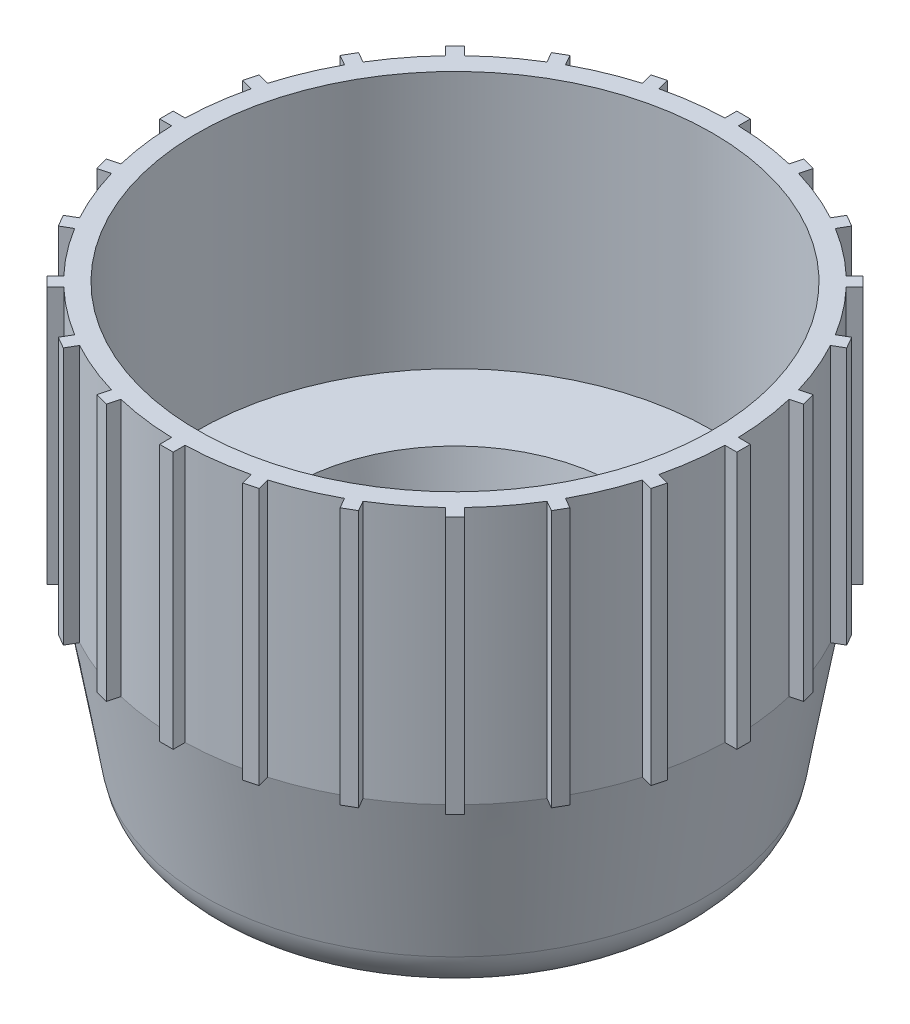
SolidWorks part; units mm, degrees
ref_plane "Front Plane" through (0, 0, 0) normal (0, 0, 1) x (1, 0, 0)
ref_plane "Top Plane" through (0, 0, 0) normal (0, 1, 0) x (1, 0, 0)
ref_plane "Right Plane" through (0, 0, 0) normal (1, 0, 0) x (0, 0, -1)
sketch "Sketch1" plane through (0, 0, 0) normal (0, 0, 1) x (1, 0, 0)
  line L0 (0, 0) -> (0, 35) construction
  line L1 (0, 0) -> (15.4987, 0)
  line L2 (19.4379, 3.3054) -> (21.5, 15)
  line L3 (10, 0) -> (12.6449, 15)
  line L4 (12.6449, 15) -> (20, 15)
  line L5 (20, 15) -> (20, 35)
  line L6 (20, 35) -> (21.5, 35)
  line L7 (21.5, 35) -> (21.5, 15)
  arc A0 (15.4987, 0) -> (19.4379, 3.3054) centre (15.4987, 4) ccw
  dimension "D8" = 4
  dimension "D1" = 35
  dimension "D2" = 20
  dimension "D3" = 100
  dimension "D4" = 20
  dimension "D5" = 40
  dimension "D6" = 43
  dimension "D7" = 80
revolve "Revolve1" add sketch "Sketch1" angle 360 about L0
sketch "Sketch2" plane through (0, 35, 0) normal (0, 1, 0) x (1, 0, 0)
  line L0 (21.4936, -0.525) -> (22.42, -0.525)
  line L1 (22.42, -0.525) -> (22.42, 0.525)
  line L2 (22.42, 0.525) -> (21.4936, 0.525)
  line L3 (20.6253, -6.0701) -> (21.5202, -6.3098)
  line L4 (21.7919, -5.2956) -> (20.8971, -5.0558)
  line L5 (21.5202, -6.3098) -> (21.7919, -5.2956)
  line L6 (18.3515, -11.2015) -> (19.1538, -11.6647)
  line L7 (19.6788, -10.7553) -> (18.8765, -10.2921)
  line L8 (19.1538, -11.6647) -> (19.6788, -10.7553)
  line L9 (14.827, -15.5695) -> (15.4821, -16.2246)
  line L10 (16.2246, -15.4821) -> (15.5695, -14.827)
  line L11 (15.4821, -16.2246) -> (16.2246, -15.4821)
  line L12 (10.2921, -18.8765) -> (10.7553, -19.6788)
  line L13 (11.6647, -19.1538) -> (11.2015, -18.3515)
  line L14 (10.7553, -19.6788) -> (11.6647, -19.1538)
  line L15 (5.0558, -20.8971) -> (5.2956, -21.7919)
  line L16 (6.3098, -21.5202) -> (6.0701, -20.6253)
  line L17 (5.2956, -21.7919) -> (6.3098, -21.5202)
  line L18 (-0.525, -21.4936) -> (-0.525, -22.42)
  line L19 (0.525, -22.42) -> (0.525, -21.4936)
  line L20 (-0.525, -22.42) -> (0.525, -22.42)
  line L21 (-6.0701, -20.6253) -> (-6.3098, -21.5202)
  line L22 (-5.2956, -21.7919) -> (-5.0558, -20.8971)
  line L23 (-6.3098, -21.5202) -> (-5.2956, -21.7919)
  line L24 (-11.2015, -18.3515) -> (-11.6647, -19.1538)
  line L25 (-10.7553, -19.6788) -> (-10.2921, -18.8765)
  line L26 (-11.6647, -19.1538) -> (-10.7553, -19.6788)
  line L27 (-15.5695, -14.827) -> (-16.2246, -15.4821)
  line L28 (-15.4821, -16.2246) -> (-14.827, -15.5695)
  line L29 (-16.2246, -15.4821) -> (-15.4821, -16.2246)
  line L30 (-18.8765, -10.2921) -> (-19.6788, -10.7553)
  line L31 (-19.1538, -11.6647) -> (-18.3515, -11.2015)
  line L32 (-19.6788, -10.7553) -> (-19.1538, -11.6647)
  line L33 (-20.8971, -5.0558) -> (-21.7919, -5.2956)
  line L34 (-21.5202, -6.3098) -> (-20.6253, -6.0701)
  line L35 (-21.7919, -5.2956) -> (-21.5202, -6.3098)
  line L36 (-21.4936, 0.525) -> (-22.42, 0.525)
  line L37 (-22.42, -0.525) -> (-21.4936, -0.525)
  line L38 (-22.42, 0.525) -> (-22.42, -0.525)
  line L39 (-20.6253, 6.0701) -> (-21.5202, 6.3098)
  line L40 (-21.7919, 5.2956) -> (-20.8971, 5.0558)
  line L41 (-21.5202, 6.3098) -> (-21.7919, 5.2956)
  line L42 (-18.3515, 11.2015) -> (-19.1538, 11.6647)
  line L43 (-19.6788, 10.7553) -> (-18.8765, 10.2921)
  line L44 (-19.1538, 11.6647) -> (-19.6788, 10.7553)
  line L45 (-14.827, 15.5695) -> (-15.4821, 16.2246)
  line L46 (-16.2246, 15.4821) -> (-15.5695, 14.827)
  line L47 (-15.4821, 16.2246) -> (-16.2246, 15.4821)
  line L48 (-10.2921, 18.8765) -> (-10.7553, 19.6788)
  line L49 (-11.6647, 19.1538) -> (-11.2015, 18.3515)
  line L50 (-10.7553, 19.6788) -> (-11.6647, 19.1538)
  line L51 (-5.0558, 20.8971) -> (-5.2956, 21.7919)
  line L52 (-6.3098, 21.5202) -> (-6.0701, 20.6253)
  line L53 (-5.2956, 21.7919) -> (-6.3098, 21.5202)
  line L54 (0.525, 21.4936) -> (0.525, 22.42)
  line L55 (-0.525, 22.42) -> (-0.525, 21.4936)
  line L56 (0.525, 22.42) -> (-0.525, 22.42)
  line L57 (6.0701, 20.6253) -> (6.3098, 21.5202)
  line L58 (5.2956, 21.7919) -> (5.0558, 20.8971)
  line L59 (6.3098, 21.5202) -> (5.2956, 21.7919)
  line L60 (11.2015, 18.3515) -> (11.6647, 19.1538)
  line L61 (10.7553, 19.6788) -> (10.2921, 18.8765)
  line L62 (11.6647, 19.1538) -> (10.7553, 19.6788)
  line L63 (15.5695, 14.827) -> (16.2246, 15.4821)
  line L64 (15.4821, 16.2246) -> (14.827, 15.5695)
  line L65 (16.2246, 15.4821) -> (15.4821, 16.2246)
  line L66 (18.8765, 10.2921) -> (19.6788, 10.7553)
  line L67 (19.1538, 11.6647) -> (18.3515, 11.2015)
  line L68 (19.6788, 10.7553) -> (19.1538, 11.6647)
  line L69 (20.8971, 5.0558) -> (21.7919, 5.2956)
  line L70 (21.5202, 6.3098) -> (20.6253, 6.0701)
  line L71 (21.7919, 5.2956) -> (21.5202, 6.3098)
  circle A0 centre (0, 0) radius 21.5 construction
  arc A1 (21.4936, -0.525) -> (21.4936, 0.525) centre (0, 0) ccw
  arc A2 (20.6253, -6.0701) -> (20.8971, -5.0558) centre (0, 0) ccw
  arc A3 (18.3515, -11.2015) -> (18.8765, -10.2921) centre (0, 0) ccw
  arc A4 (14.827, -15.5695) -> (15.5695, -14.827) centre (0, 0) ccw
  arc A5 (10.2921, -18.8765) -> (11.2015, -18.3515) centre (0, 0) ccw
  arc A6 (5.0558, -20.8971) -> (6.0701, -20.6253) centre (0, 0) ccw
  arc A7 (-0.525, -21.4936) -> (0.525, -21.4936) centre (0, 0) ccw
  arc A8 (-6.0701, -20.6253) -> (-5.0558, -20.8971) centre (0, 0) ccw
  arc A9 (-11.2015, -18.3515) -> (-10.2921, -18.8765) centre (0, 0) ccw
  arc A10 (-15.5695, -14.827) -> (-14.827, -15.5695) centre (0, 0) ccw
  arc A11 (-18.8765, -10.2921) -> (-18.3515, -11.2015) centre (0, 0) ccw
  arc A12 (-20.8971, -5.0558) -> (-20.6253, -6.0701) centre (0, 0) ccw
  arc A13 (-21.4936, 0.525) -> (-21.4936, -0.525) centre (0, 0) ccw
  arc A14 (-20.6253, 6.0701) -> (-20.8971, 5.0558) centre (0, 0) ccw
  arc A15 (-18.3515, 11.2015) -> (-18.8765, 10.2921) centre (0, 0) ccw
  arc A16 (-14.827, 15.5695) -> (-15.5695, 14.827) centre (0, 0) ccw
  arc A17 (-10.2921, 18.8765) -> (-11.2015, 18.3515) centre (0, 0) ccw
  arc A18 (-5.0558, 20.8971) -> (-6.0701, 20.6253) centre (0, 0) ccw
  arc A19 (0.525, 21.4936) -> (-0.525, 21.4936) centre (0, 0) ccw
  arc A20 (6.0701, 20.6253) -> (5.0558, 20.8971) centre (0, 0) ccw
  arc A21 (11.2015, 18.3515) -> (10.2921, 18.8765) centre (0, 0) ccw
  arc A22 (15.5695, 14.827) -> (14.827, 15.5695) centre (0, 0) ccw
  arc A23 (18.8765, 10.2921) -> (18.3515, 11.2015) centre (0, 0) ccw
  arc A24 (20.8971, 5.0558) -> (20.6253, 6.0701) centre (0, 0) ccw
  point P4 (22.42, 0)
  point P102 (0, 0)
  dimension "D1" = 1.05
  dimension "D2" = 22.42
  dimension "D3" = 24
extrude "Boss-Extrude1" add sketch "Sketch2" against normal blind 20
